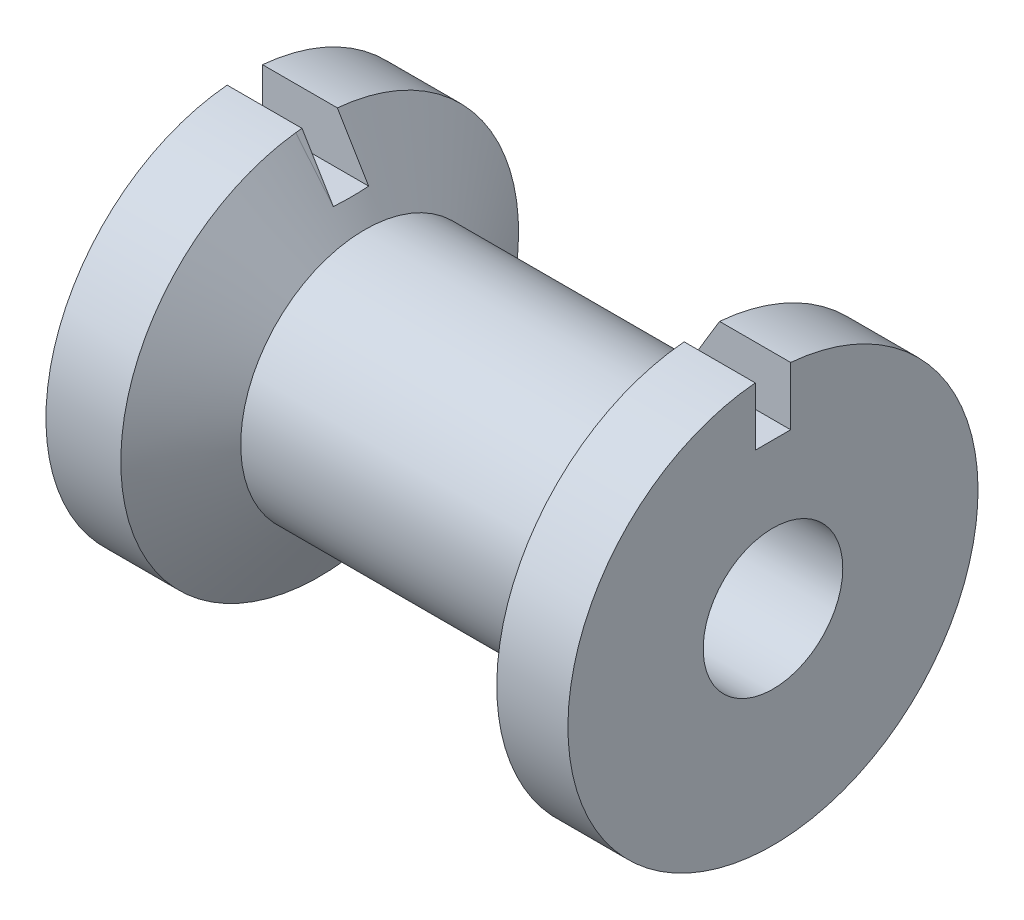
SolidWorks part; units mm, degrees
ref_plane "Front Plane" through (0, 0, 0) normal (0, 0, 1) x (1, 0, 0)
ref_plane "Top Plane" through (0, 0, 0) normal (0, 1, 0) x (1, 0, 0)
ref_plane "Right Plane" through (0, 0, 0) normal (1, 0, 0) x (0, 0, -1)
sketch "Sketch1" plane through (0, 0, 0) normal (0, 0, 1) x (1, 0, 0)
  line L1 (-12.3858, 10.6691) -> (-16.2661, 17.0976)
  line L2 (-12.3858, 10.6691) -> (12.3858, 10.6691)
  line L3 (16.5859, 17.6273) -> (22.7017, 17.6273)
  line L4 (22.7017, 17.6273) -> (22.7017, 0)
  line L5 (22.7017, 0) -> (-22.7017, 0)
  line L6 (-22.7017, 17.0976) -> (-22.7017, 0)
  line L7 (-16.2661, 17.0976) -> (-22.7017, 17.0976)
  line L8 (12.3858, 10.6691) -> (16.5859, 17.6273)
revolve "Revolve2" add sketch "Sketch1" angle 360 about L5
sketch "Sketch2" plane through (22.7017, 0, 0) normal (1, 0, 0) x (0, 0, -1)
  line L1 (-1.5211, 22.705) -> (1.5211, 22.705)
  line L2 (-1.5211, 22.705) -> (-1.5211, 12.5497)
  line L3 (-1.5211, 12.5497) -> (1.5211, 12.5497)
  line L4 (1.5211, 22.705) -> (1.5211, 12.5497)
  line L5 (-1.5211, 22.705) -> (1.5211, 12.5497) construction
  line L6 (-1.5211, 12.5497) -> (1.5211, 22.705) construction
  circle A0 centre (0, 0) radius 6
  circle A1 centre (0, 0) radius 17.6273 construction
  point P3 (0, 17.6273)
extrude "Cut-Extrude1" cut sketch "Sketch2" against normal through all
